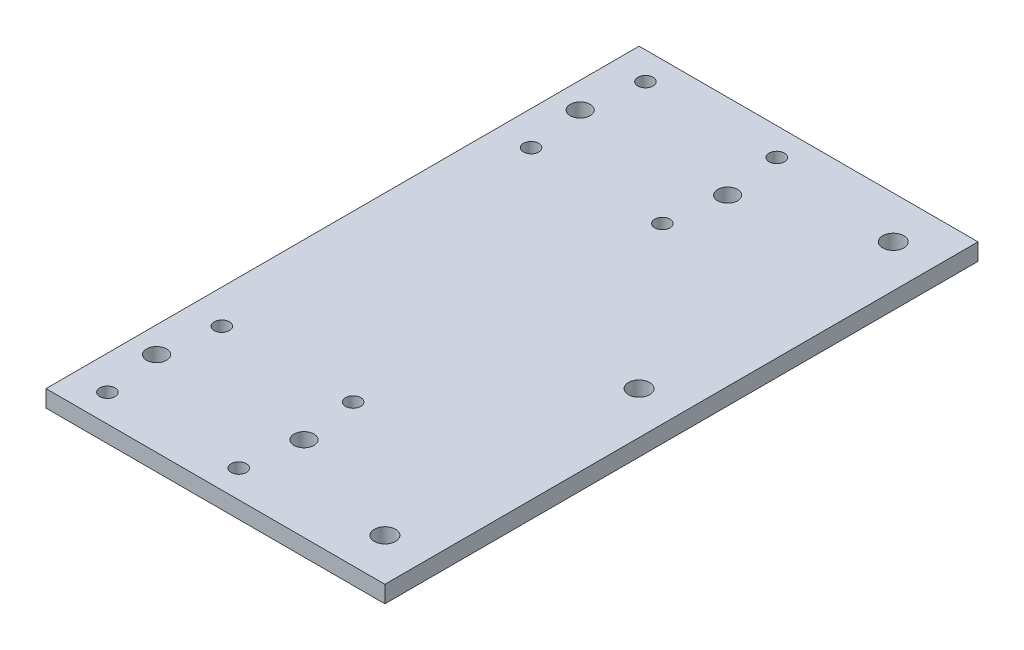
SolidWorks part; units mm, degrees
ref_plane "前视基准面" through (0, 0, 0) normal (0, 0, 1) x (1, 0, 0)
ref_plane "上视基准面" through (0, 0, 0) normal (0, 1, 0) x (1, 0, 0)
ref_plane "右视基准面" through (0, 0, 0) normal (1, 0, 0) x (0, 0, -1)
other "Configuration Table"
sketch "草图2" plane through (0, 0, 0) normal (0, 1, 0) x (1, 0, 0)
  line L0 (0, 70) -> (0, -70)
  line L1 (-80, -70) -> (80, -70)
  line L2 (-80, -70) -> (-80, 70)
  line L3 (-80, 70) -> (80, 70)
  line L4 (80, -70) -> (80, 70)
  line L5 (-80, -70) -> (80, 70) construction
  line L6 (-80, 70) -> (80, -70) construction
  point P0 (0, 0)
  dimension "D1" = 140
  dimension "D2" = 160
extrude "凸台-拉伸1" add sketch "草图2" along normal blind 4 contours L3 L2 L1 L0
ref_plane "基准面1" through (0, 4, 0) normal (0, 1, 0) x (1, 0, 0)
sketch "草图3" plane through (0, 4, 0) normal (0, 1, 0) x (1, 0, 0)
  line L0 (-1080, 50) -> (48920, 50) construction
  line L1 (-80, 70) -> (-33, 70)
  line L2 (-80, 70) -> (-80, 30)
  line L3 (-80, 30) -> (-33, 30)
  line L4 (-33, 70) -> (-33, 30)
  line L5 (-80, -70) -> (-33, -70)
  line L6 (-80, -70) -> (-80, -30)
  line L7 (-80, -30) -> (-33, -30)
  line L8 (-33, -70) -> (-33, -30)
  line L9 (-56.5, 110.6134) -> (-56.5, 29.3866) construction
  line L10 (-80, 0) -> (49920, 0) construction
  line L11 (-80, -70) -> (-80, 70) construction
  line L12 (0, 70) -> (0, -70) construction
  line L13 (-80, 70) -> (0, 70) construction
  line L14 (0, 70) -> (-10, 70)
  line L15 (0, 70) -> (0, 60)
  line L16 (0, 60) -> (-10, 60)
  line L17 (-10, 70) -> (-10, 60)
  circle A0 centre (-72, 63.5) radius 1.8
  circle A1 centre (-41, 63.5) radius 1.8
  circle A2 centre (-41, 36.5) radius 1.8
  circle A3 centre (-72, 36.5) radius 1.8
  circle A4 centre (-41, -63.5) radius 1.8
  circle A5 centre (-41, -36.5) radius 1.8
  circle A6 centre (-72, -36.5) radius 1.8
  circle A7 centre (-72, -63.5) radius 1.8
  circle A8 centre (-73.9, 50) radius 2.35
  circle A9 centre (-73.9, -50) radius 2.35
  circle A10 centre (-39.1, -50) radius 2.35
  circle A11 centre (-39.1, 50) radius 2.35
  circle A12 centre (-10, 60) radius 2.5
  circle A13 centre (-10, 0) radius 2.5
  circle A14 centre (-10, -60) radius 2.5
  point P13 (-80, 50)
  point P18 (-56.5, 70)
  point P28 (-80, 0)
  point P31 (0, 0)
  dimension "D5" = 3.6
  dimension "D8" = 4.7
  dimension "D10" = 10
  dimension "D12" = 5
  dimension "D1" = 40
  dimension "D2" = 40
  dimension "D3" = 47
  dimension "D4" = 47
  dimension "D6" = 8
  dimension "D7" = 6.5
  dimension "D9" = 6.1
  dimension "D11" = 10
  dimension "D13" = 3
extrude "切除-拉伸3" cut sketch "草图3" against normal blind 4 contours A0 | A8 | A3 | A2 | A11 | A1 | L16 A12 L17 | L17 A12 L16 | A9 | A6 | A7 | A4 | A10 | A5 | A14 | A13
